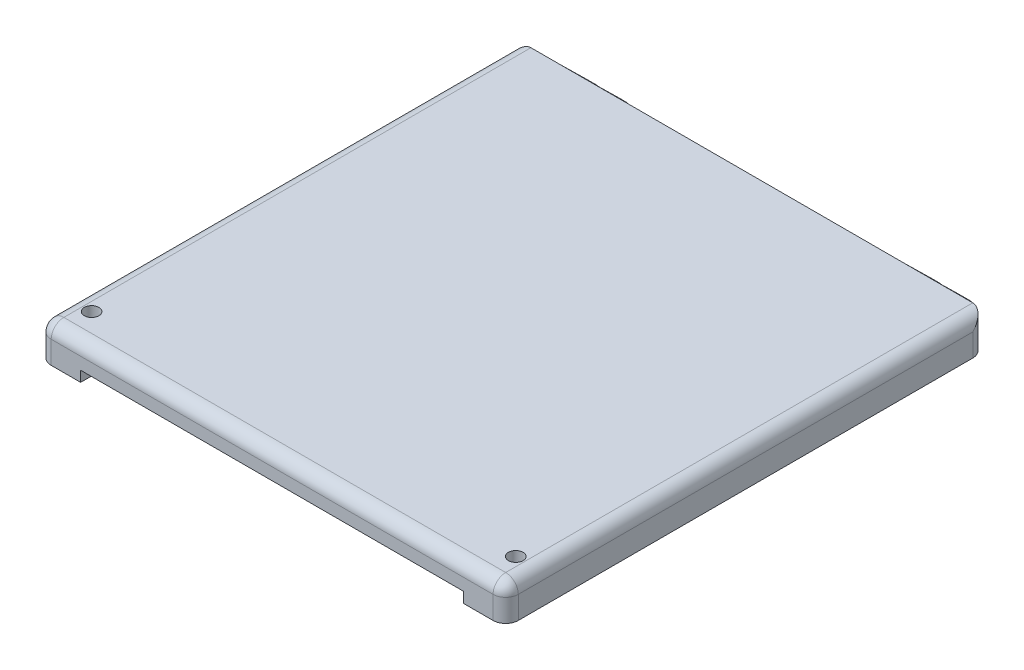
SolidWorks part; units mm, degrees
ref_plane "Front Plane" through (0, 0, 0) normal (0, 0, 1) x (1, 0, 0)
ref_plane "Top Plane" through (0, 0, 0) normal (0, 1, 0) x (1, 0, 0)
ref_plane "Right Plane" through (0, 0, 0) normal (1, 0, 0) x (0, 0, -1)
sketch "Sketch1" plane through (0, 0, 0) normal (0, 1, 0) x (1, 0, 0)
  line L1 (-70.485, -72.39) -> (70.485, -72.39)
  line L2 (-70.485, -72.39) -> (-70.485, 72.39)
  line L3 (-70.485, 72.39) -> (70.485, 72.39)
  line L4 (70.485, -72.39) -> (70.485, 72.39)
  line L5 (-70.485, -72.39) -> (70.485, 72.39) construction
  line L6 (-70.485, 72.39) -> (70.485, -72.39) construction
  point P0 (0, 0)
  dimension "D1" = 144.78
  dimension "D2" = 140.97
extrude "Boss-Extrude1" add sketch "Sketch1" along normal blind 5.08
sketch "Sketch2" plane through (0, 0, 0) normal (0, -1, 0) x (1, 0, 0)
  line L0 (-70.485, 72.39) -> (70.485, 72.39) construction
  line L1 (-57.785, 56.515) -> (57.785, 56.515)
  line L2 (-57.785, 56.515) -> (-57.785, 69.215)
  line L3 (-57.785, 69.215) -> (57.785, 69.215)
  line L4 (57.785, 56.515) -> (57.785, 69.215)
  line L5 (-57.785, 56.515) -> (57.785, 69.215) construction
  line L6 (-57.785, 69.215) -> (57.785, 56.515) construction
  line L7 (-70.485, -72.39) -> (-70.485, 72.39) construction
  line L8 (70.485, -72.39) -> (-70.485, -72.39) construction
  line L9 (70.485, 72.39) -> (70.485, -72.39) construction
  line L10 (-70.485, 72.39) -> (70.485, 72.39)
  line L11 (-70.485, -72.39) -> (-70.485, 72.39)
  line L12 (70.485, -72.39) -> (-70.485, -72.39)
  line L13 (70.485, 72.39) -> (70.485, -72.39)
  line L15 (-65.405, 53.34) -> (65.405, 53.34)
  line L16 (-65.405, 53.34) -> (-65.405, -67.31)
  line L17 (-65.405, -67.31) -> (65.405, -67.31)
  line L18 (65.405, 53.34) -> (65.405, -67.31)
  point P0 (0, 62.865)
  dimension "D1" = 5.08
  dimension "D2" = 5.08
  dimension "D3" = 12.7
  dimension "D4" = 5.08
  dimension "D5" = 3.175
  dimension "D6" = 12.7
  dimension "D7" = 12.7
  dimension "D8" = 3.175
extrude "Boss-Extrude2" add sketch "Sketch2" along normal blind 5.5562
sketch "Sketch3" plane through (0, -5.5562, 0) normal (0, -1, 0) x (1, 0, 0)
  line L0 (70.485, 72.39) -> (-70.485, 72.39) construction
  line L1 (-57.785, 72.39) -> (57.785, 72.39)
  line L2 (-57.785, 72.39) -> (-57.785, 53.34)
  line L3 (-57.785, 53.34) -> (57.785, 53.34)
  line L4 (57.785, 72.39) -> (57.785, 53.34)
  line L5 (65.405, 53.34) -> (-65.405, 53.34) construction
  line L6 (-57.785, 69.215) -> (-57.785, 56.515) construction
  line L7 (57.785, 56.515) -> (57.785, 69.215) construction
extrude "Cut-Extrude1" cut sketch "Sketch3" against normal blind 3.175
ref_plane "Plane1" through (57.785, 0, 0) normal (1, 0, 0) x (0, 0, -1)
sketch "Sketch4" plane through (57.785, 0, 0) normal (1, 0, 0) x (0, 0, -1)
  line L1 (79.4907, -2.0563) -> (75.4493, -2.0562) construction
  line L2 (75.4493, -2.0562) -> (73.4285, -5.5562) construction
  line L3 (73.4285, -5.5562) -> (75.4493, -9.0562) construction
  line L4 (75.4493, -9.0562) -> (79.4907, -9.0562) construction
  line L5 (79.4907, -9.0562) -> (81.5115, -5.5562) construction
  line L6 (81.5115, -5.5562) -> (79.4907, -2.0563) construction
  line L7 (72.39, 5.08) -> (72.39, -5.5562) construction
  line L8 (72.39, -5.5562) -> (-72.39, -5.5562) construction
  line L9 (72.39, 5.08) -> (80.2986, -2.6697)
  line L10 (74.2548, -8.0049) -> (72.39, -5.5562)
  line L11 (72.39, 5.08) -> (72.39, -5.5562)
  circle A0 centre (77.47, -5.5562) radius 4.0415 construction
  circle A1 centre (77.47, -5.5562) radius 2.2
  arc A2 (80.2986, -2.6697) -> (74.2548, -8.0049) centre (77.47, -5.5562) cw
  dimension "D3" = 4.4
  dimension "D1" = 7
  dimension "D2" = 5.08
extrude "Boss-Extrude3" add sketch "Sketch4" against normal blind 3
ref_plane "Plane2" through (51.785, 0, 0) normal (-1, 0, 0) x (0, 0, 1)
mirror "Mirror1" about plane through (51.785, 0, 0) normal (-1, 0, 0) of "Boss-Extrude3"
mirror "Mirror2" about plane through (0, 0, 0) normal (1, 0, 0) of "Boss-Extrude3", "Mirror1"
sketch "Sketch5" plane through (0, 5.08, 0) normal (0, 1, 0) x (1, 0, 0)
  line L0 (0, 0) -> (0, -50000) construction
  line L1 (-70.485, -72.39) -> (70.485, -72.39) construction
  circle A0 centre (64.008, -62.865) radius 2.2
  circle A1 centre (-64.008, -62.865) radius 2.2
  dimension "D2" = 9.525
  dimension "D3" = 4.4
  dimension "D1" = 128.016
extrude "Cut-Extrude2" cut sketch "Sketch5" against normal through all
sketch "Sketch6" plane through (0, -5.5562, 0) normal (0, -1, 0) x (1, 0, 0)
  circle A0 centre (-64.008, 62.865) radius 4.572
  circle A1 centre (64.008, 62.865) radius 4.572
  dimension "D1" = 9.144
extrude "Cut-Extrude3" cut sketch "Sketch6" against normal blind 2.54
fillet "Fillet1" radius 3.81 7 edges at (-70.485, 5.08, 0) (0, 5.08, 72.39) (70.485, 5.08, 0) (70.485, -0.2381, 72.39) (-70.485, -0.2381, 72.39) (-70.485, -0.2381, -72.39) (70.485, -0.2381, -72.39)
